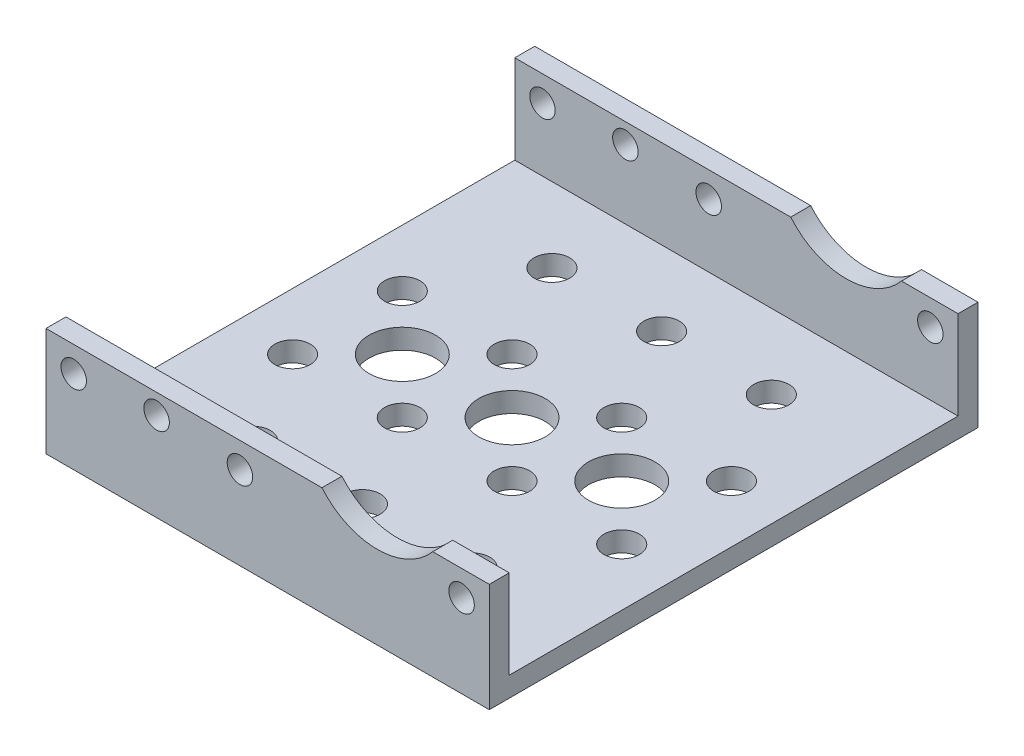
SolidWorks part; units mm, degrees
ref_plane "前视基准面" through (0, 0, 0) normal (0, 0, 1) x (1, 0, 0)
ref_plane "上视基准面" through (0, 0, 0) normal (0, 1, 0) x (1, 0, 0)
ref_plane "右视基准面" through (0, 0, 0) normal (1, 0, 0) x (0, 0, -1)
sketch "草图1" plane through (0, 0, 0) normal (0, 1, 0) x (1, 0, 0)
  line L1 (-20, -20.25) -> (20, -20.25)
  line L2 (-20, -20.25) -> (-20, 20.25)
  line L3 (-20, 20.25) -> (20, 20.25)
  line L4 (20, -20.25) -> (20, 20.25)
  line L5 (-20, -20.25) -> (20, 20.25) construction
  line L6 (-20, 20.25) -> (20, -20.25) construction
  point P0 (0, 0)
  dimension "D1" = 40.5
  dimension "D2" = 40
extrude "凸台-拉伸1" add sketch "草图1" along normal blind 1.8
sketch "草图2" plane through (0, 1.8, 0) normal (0, 1, 0) x (1, 0, 0)
  circle A0 centre (-9.9, 13.5) radius 1.6
  circle A1 centre (0, 13.5) radius 1.6
  circle A2 centre (9.9, 13.5) radius 1.6
  circle A3 centre (0, 0) radius 3
  circle A4 centre (9.9, 0) radius 3
  circle A5 centre (-9.9, 0) radius 3
  circle A6 centre (-9.9, -13.5) radius 1.6
  circle A7 centre (0, -13.5) radius 1.6
  circle A8 centre (9.9, -13.5) radius 1.6
  circle A9 centre (0, 0) radius 7 construction
  circle A10 centre (-9.9, 0) radius 7 construction
  circle A11 centre (9.9, 0) radius 7 construction
  circle A12 centre (-4.95, 4.9495) radius 1.6
  circle A13 centre (4.95, 4.9495) radius 1.6
  circle A14 centre (14.8495, 4.95) radius 1.6
  circle A15 centre (14.85, -4.9495) radius 1.6
  circle A16 centre (4.9505, -4.95) radius 1.6
  circle A17 centre (-4.9505, -4.95) radius 1.6
  circle A18 centre (-14.85, -4.9495) radius 1.6
  circle A19 centre (-14.8495, 4.95) radius 1.6
  point P35 (9.9, 0)
  point P42 (-9.9, 0)
  dimension "D1" = 13.5
  dimension "D3" = 6
  dimension "D4" = 6
  dimension "D5" = 6
  dimension "D6" = 4
  dimension "D2" = 9.9
  dimension "D7" = 4
extrude "切除-拉伸1" cut sketch "草图2" against normal blind 2
sketch "草图3" plane through (0, 0, 20.25) normal (0, 0, 1) x (1, 0, 0)
  line L1 (-20, 0) -> (20, 0)
  line L2 (-20, 0) -> (-20, 9.8)
  line L3 (-20, 9.8) -> (20, 9.8)
  line L4 (20, 0) -> (20, 9.8)
  dimension "D1" = 9.8
extrude "凸台-拉伸2" add sketch "草图3" along normal blind 1.8
sketch "草图4" plane through (0, 0, 22.05) normal (0, 0, 1) x (1, 0, 0)
  line L0 (-20, 9.8) -> (-20, 0) construction
  line L1 (-20, 0) -> (20, 0) construction
  line L2 (20, 9.8) -> (-20, 9.8) construction
  line L3 (14.9, 9.8) -> (4.9, 9.8)
  circle A0 centre (-17.5, 7.5) radius 1.15
  circle A1 centre (-2.5, 7.5) radius 1.15
  circle A2 centre (17.5, 7.5) radius 1.15
  circle A3 centre (-10.02, 8) radius 1.15
  arc A4 (14.9, 9.8) -> (4.9, 9.8) centre (9.9, 14.029) cw
  point P12 (9.9, 7.5)
  point P13 (4.9, 9.8)
  point P14 (14.9, 9.8)
  dimension "D1" = 2.5
  dimension "D5" = 7.48
  dimension "D2" = 7.5
  dimension "D6" = 0.5
  dimension "D7" = 9.9
  dimension "D8" = 5
  dimension "D9" = 5
  dimension "D3" = 2
  dimension "D4" = 2
extrude "切除-拉伸2" cut sketch "草图4" against normal blind 1.8
ref_plane "基准面1" through (0, 0, 0) normal (0, 0, 1) x (1, 0, 0)
mirror "镜向1" about plane through (0, 0, 0) normal (0, 0, 1) of "凸台-拉伸2", "切除-拉伸2"
